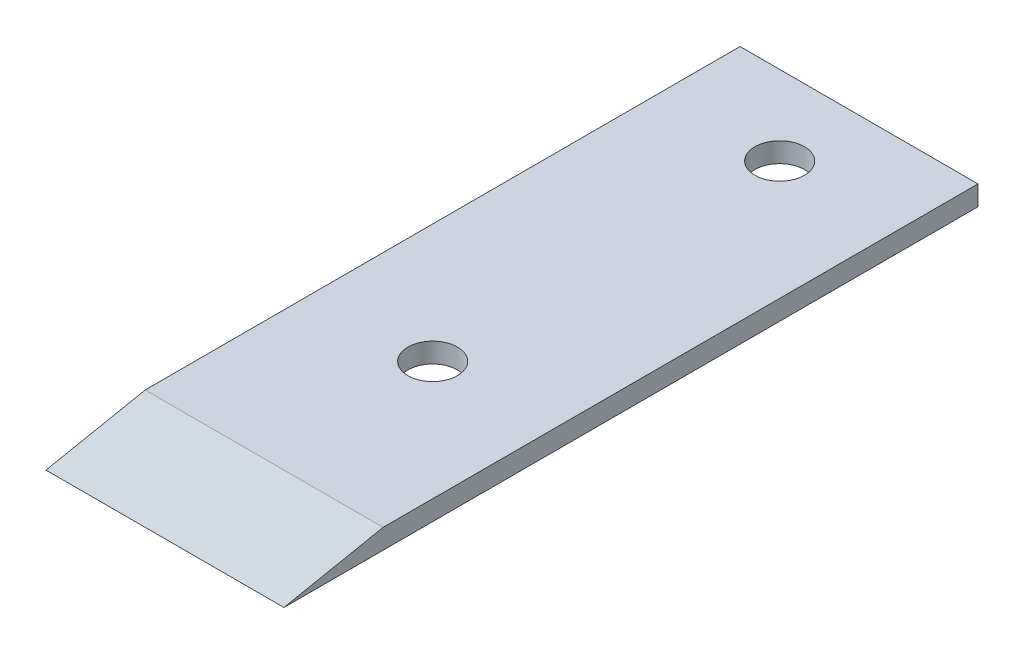
SolidWorks part; units mm, degrees
ref_plane "前视基准面" through (0, 0, 0) normal (0, 0, 1) x (1, 0, 0)
ref_plane "上视基准面" through (0, 0, 0) normal (0, 1, 0) x (1, 0, 0)
ref_plane "右视基准面" through (0, 0, 0) normal (1, 0, 0) x (0, 0, -1)
sketch "草图1" plane through (0, 0, 0) normal (0, 1, 0) x (1, 0, 0)
  line L1 (-12, -35) -> (12, -35)
  line L2 (-12, -35) -> (-12, 35)
  line L3 (-12, 35) -> (12, 35)
  line L4 (12, -35) -> (12, 35)
  line L5 (-12, -35) -> (12, 35) construction
  line L6 (-12, 35) -> (12, -35) construction
  point P0 (0, 0)
  dimension "D1" = 24
  dimension "D2" = 70
extrude "凸台-拉伸1" add sketch "草图1" along normal blind 2
sketch "草图2" plane through (0, 2, 0) normal (0, 1, 0) x (1, 0, 0)
  line L0 (0, -1.1) -> (0, 1.1) construction
  line L1 (12, 35) -> (-12, 35) construction
  circle A0 centre (0, -8) radius 2.5
  circle A1 centre (0, 27) radius 2.5
  dimension "D1" = 5
  dimension "D2" = 5
  dimension "D3" = 8
  dimension "D4" = 35
extrude "切除-拉伸1" cut sketch "草图2" against normal through all
sketch "草图3" plane through (12, 0, 0) normal (1, 0, 0) x (0, 0, -1)
  line L0 (-35, 0) -> (-25, 2)
  line L1 (-35, 2) -> (35, 2) construction
  line L2 (-35, 2) -> (-35, 0) construction
  dimension "D1" = 10
extrude "切除-拉伸2" cut sketch "草图3" against normal through all and the other way through all
